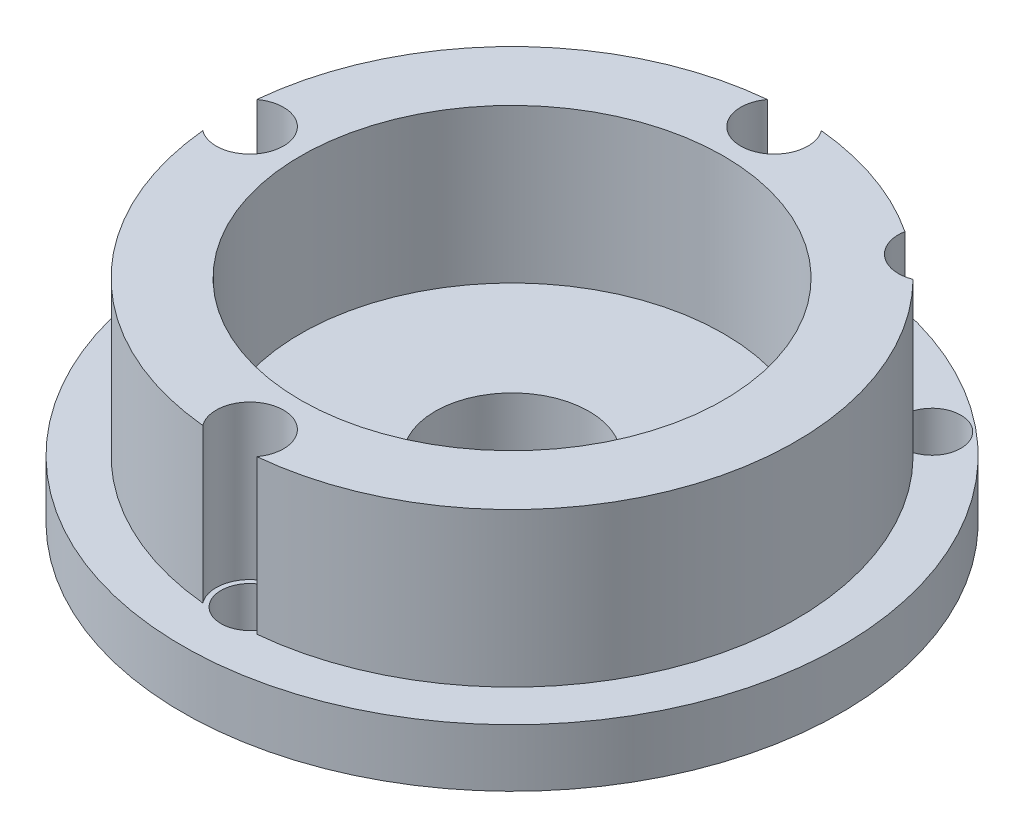
SolidWorks part; units mm, degrees
ref_plane "Alzado" through (0, 0, 0) normal (0, 0, 1) x (1, 0, 0)
ref_plane "Planta" through (0, 0, 0) normal (0, 1, 0) x (1, 0, 0)
ref_plane "Vista lateral" through (0, 0, 0) normal (1, 0, 0) x (0, 0, -1)
sketch "Croquis1" plane through (0, 0, 0) normal (0, 0, 1) x (1, 0, 0)
  line L0 (-4, 0) -> (-4, 7)
  line L1 (-4, 7) -> (-5, 7)
  line L3 (-14, 0) -> (-4, 0)
  line L4 (0, 0) -> (0, 7.6146) construction
  line L5 (-14, 0) -> (-17.1429, 0)
  line L6 (-17.1429, 0) -> (-17.1429, 3)
  line L7 (-17.1429, 3) -> (-10.1429, 3)
  line L8 (-10.1429, 3) -> (-5, 7)
  dimension "D1" = 10
  dimension "D2" = 7
  dimension "D3" = 1
  dimension "D4" = 4
  dimension "D5" = 7
revolve "Revolución1" add sketch "Croquis1" angle 360 about L4
sketch "Croquis2" plane through (0, 3, 0) normal (0, 1, 0) x (1, 0, 0)
  circle A0 centre (0, 13.64) radius 1.5
  circle A1 centre (13.64, 0) radius 1.5
  circle A2 centre (0, -13.64) radius 1.5
  circle A3 centre (-13.64, 0) radius 1.5
  dimension "D1" = 13.64
  dimension "D2" = 13.64
  dimension "D3" = 13.64
  dimension "D4" = 13.64
extrude "Cortar-Extruir1" cut sketch "Croquis2" against normal blind 10
sketch "Croquis3" plane through (0, 3, 0) normal (0, 1, 0) x (1, 0, 0)
  circle A0 centre (13.64, 0) radius 1.5
extrude "Saliente-Extruir1" add sketch "Croquis3" against normal blind 3
sketch "Croquis4" plane through (0, 0, 0) normal (0, -1, 0) x (-1, 0, 0)
  line L0 (-9.8447, 11.998) -> (0, 0)
  line L1 (0, 0) -> (0, 13.64)
  circle A0 centre (-9.8447, 11.998) radius 1.5
  dimension "D1" = 39.37
  dimension "D2" = 15.52
extrude "Cortar-Extruir2" cut sketch "Croquis4" against normal blind 10
sketch "Croquis5" plane through (0, 7, 0) normal (0, 1, 0) x (1, 0, 0)
  circle A0 centre (0, 0) radius 11.75
  circle A1 centre (0, 0) radius 14.75
  dimension "D1" = 29.5
extrude "Saliente-Extruir2" add sketch "Croquis5" against normal blind 4 and the other way blind 4
sketch "Croquis6" plane through (0, 0, 0) normal (0, -1, 0) x (-1, 0, 0)
  circle A0 centre (13.64, 0) radius 1.5
  circle A1 centre (0, -13.64) radius 1.5
  circle A2 centre (-9.8447, 11.998) radius 1.5
  circle A3 centre (0, 13.64) radius 1.5
extrude "Cortar-Extruir3" cut sketch "Croquis6" against normal blind 12
sketch "Croquis8" plane through (0, 3, 0) normal (0, 1, 0) x (1, 0, 0)
  circle A0 centre (0, 0) radius 10.1429
extrude "Cortar-Extruir4" cut sketch "Croquis8" along normal blind 9
sketch "Croquis9" plane through (0, 11, 0) normal (0, 1, 0) x (1, 0, 0)
  circle A0 centre (9.8447, 11.998) radius 1.75
  circle A1 centre (0, 13.64) radius 1.75
  circle A2 centre (-13.64, 0) radius 1.75
  circle A3 centre (0, -13.64) radius 1.75
extrude "Cortar-Extruir6" cut sketch "Croquis9" against normal blind 8
sketch "Croquis10" plane through (0, 11, 0) normal (0, 1, 0) x (1, 0, 0)
  circle A0 centre (0, 0) radius 11.75
  circle A1 centre (0, 0) radius 11.125
extrude "Saliente-Extruir3" add sketch "Croquis10" against normal blind 10
sketch "Croquis11" plane through (0, 11, 0) normal (0, 1, 0) x (1, 0, 0)
  circle A0 centre (0, 0) radius 11.125
  circle A1 centre (0, 0) radius 11
extrude "Saliente-Extruir4" add sketch "Croquis11" against normal blind 10
